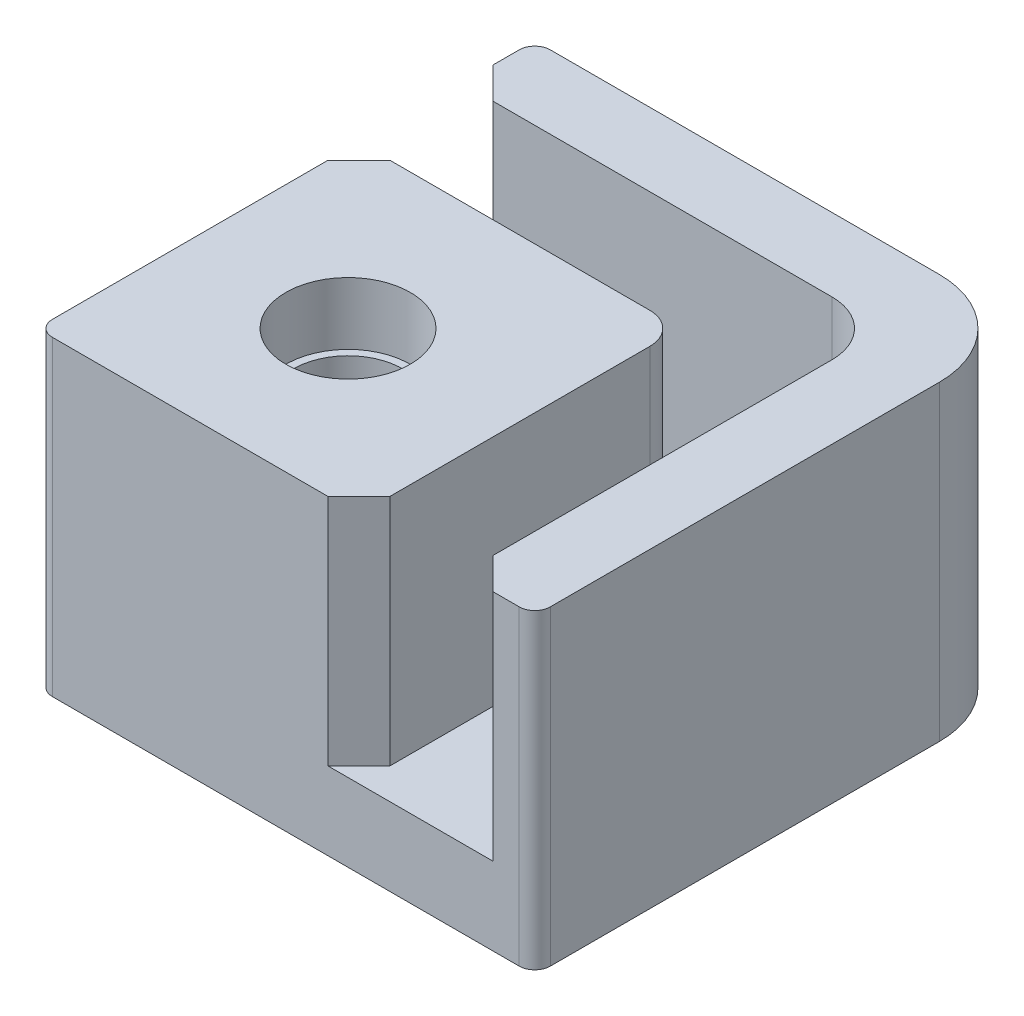
SolidWorks part; units mm, degrees
ref_plane "Front Plane" through (0, 0, 0) normal (0, 0, 1) x (1, 0, 0)
ref_plane "Top Plane" through (0, 0, 0) normal (0, 1, 0) x (1, 0, 0)
ref_plane "Right Plane" through (0, 0, 0) normal (1, 0, 0) x (0, 0, -1)
sketch "Sketch1" plane through (0, 0, 0) normal (0, 1, 0) x (1, 0, 0)
  line L1 (0, 0) -> (16, 0)
  line L2 (0, 0) -> (0, -16)
  line L3 (0, -16) -> (16, -16)
  line L4 (16, 0) -> (16, -16)
  dimension "D1" = 16
  dimension "D2" = 16
extrude "Boss-Extrude1" add sketch "Sketch1" along normal blind 10
sketch "Sketch4" plane through (0, 10, 0) normal (0, 1, 0) x (1, 0, 0)
  line L0 (0, 0) -> (0, -16) construction
  line L2 (0, -16) -> (16, -16) construction
  circle A0 centre (5, -11) radius 1.75
  dimension "D3" = 3.5
  dimension "D1" = 5
  dimension "D2" = 5
extrude "Cut-Extrude3" cut sketch "Sketch4" against normal blind 10
sketch "Sketch5" plane through (0, 10, 0) normal (0, 1, 0) x (1, 0, 0)
  line L1 (0, -2.35) -> (13.65, -2.35)
  line L2 (0, -2.35) -> (0, -5.65)
  line L3 (0, -5.65) -> (10.35, -5.65)
  line L4 (0, -16) -> (16, -16) construction
  line L5 (13.65, -16) -> (10.35, -16)
  line L6 (13.65, -16) -> (13.65, -2.35)
  line L7 (0, 0) -> (0, -16) construction
  line L8 (10.35, -16) -> (10.35, -5.65)
  point P9 (12, -16)
  point P11 (0, -4)
  dimension "D1" = 3.3
  dimension "D2" = 12
  dimension "D3" = 12
extrude "Cut-Extrude4" cut sketch "Sketch5" against normal blind 7.5
fillet "Fillet1" radius 1 1 edges at (10.35, 6.25, 5.65)
fillet "Fillet2" radius 1.75 1 edges at (13.65, 6.25, 2.35)
fillet "Fillet5" radius 3 1 edges at (16, 5, 0)
chamfer "Chamfer1" distance 1 angle 45 4 edges at (10.35, 6.25, 16) (13.65, 6.25, 16) (0, 6.25, 5.65) (0, 6.25, 2.35)
fillet "Fillet6" radius 0.5 3 edges at (16, 5, 16) (0, 5, 16) (0, 5, 0)
sketch "Sketch6" plane through (0, 10, 0) normal (0, 1, 0) x (1, 0, 0)
  circle A0 centre (5, -11) radius 2
  dimension "D1" = 4
extrude "Cut-Extrude5" cut sketch "Sketch6" against normal blind 2
